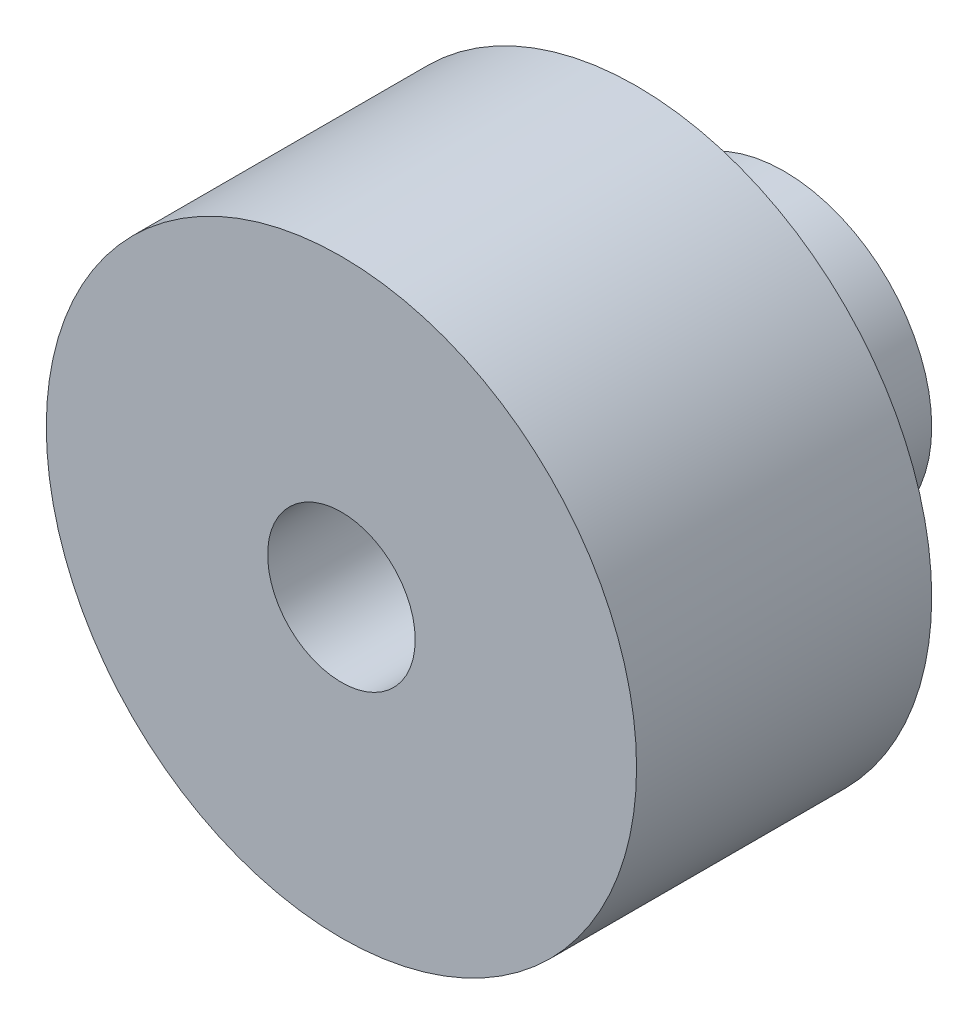
SolidWorks part; units mm, degrees
ref_plane "Front Plane" through (0, 0, 0) normal (0, 0, 1) x (1, 0, 0)
ref_plane "Top Plane" through (0, 0, 0) normal (0, 1, 0) x (1, 0, 0)
ref_plane "Right Plane" through (0, 0, 0) normal (1, 0, 0) x (0, 0, -1)
sketch "Sketch1" plane through (0, 0, 0) normal (0, 0, 1) x (1, 0, 0)
  circle A0 centre (0, 0) radius 20
  point P3 (0, 0)
  dimension "D1" = 40
extrude "Boss-Extrude1" add sketch "Sketch1" along normal blind 20
sketch "Sketch2" plane through (0, 0, 20) normal (0, 0, 1) x (1, 0, 0)
  circle A2 centre (0, 0) radius 5
  dimension "D1" = 10
extrude "Cut-Extrude1" cut sketch "Sketch2" against normal up to surface (20 mm away) up to face at (20, 0, 0)
sketch "Sketch3" plane through (0, 0, 0) normal (0, 0, -1) x (-1, 0, 0)
  circle A0 centre (0, 0) radius 5
  circle A1 centre (0, 0) radius 10
  dimension "D1" = 20
  dimension "D2" = 10
extrude "Boss-Extrude2" add sketch "Sketch3" along normal blind 10
ref_plane "Plane1" through (10, 0, 0) normal (1, 0, 0) x (0, 0, -1)
sketch "Sketch5" plane through (10, 0, 0) normal (1, 0, 0) x (0, 0, -1)
  line L0 (10, -5) -> (10, 5) construction
  circle A0 centre (5, 0) radius 1
  point P4 (5, 0)
  point P5 (0, 0)
  dimension "D1" = 2
  dimension "D2" = 5
extrude "Cut-Extrude2" cut sketch "Sketch5" against normal up to surface (5 mm away) up to face at (5, 0, 20)
